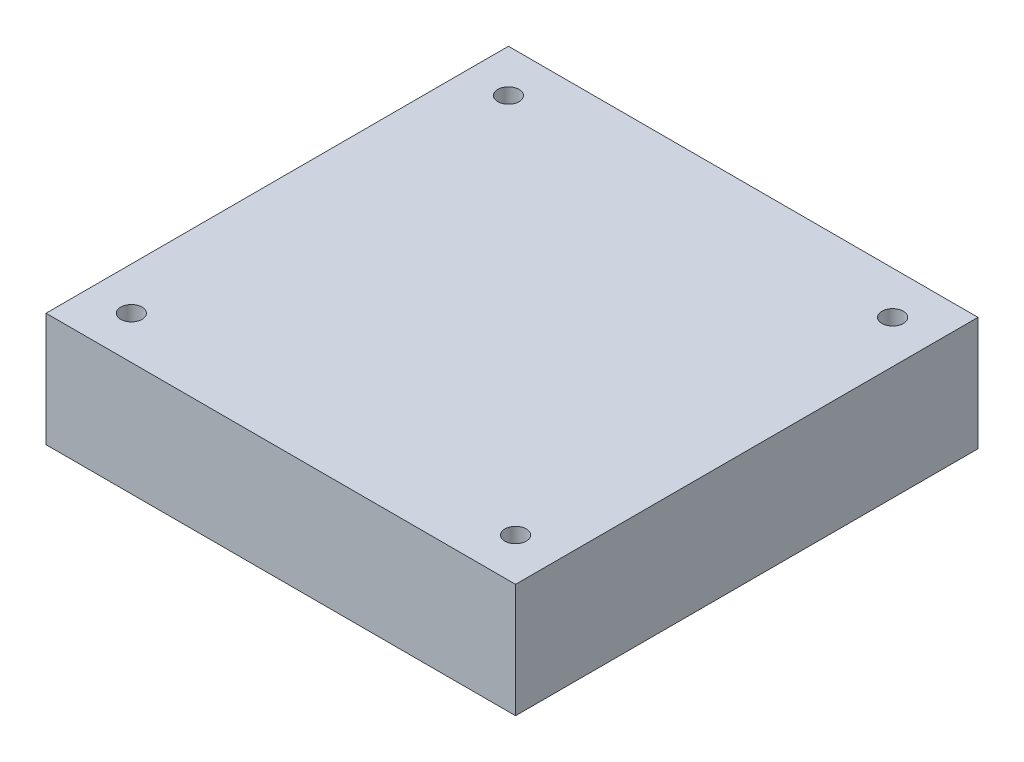
SolidWorks part; units mm, degrees
ref_plane "Front Plane" through (0, 0, 0) normal (0, 0, 1) x (1, 0, 0)
ref_plane "Top Plane" through (0, 0, 0) normal (0, 1, 0) x (1, 0, 0)
ref_plane "Right Plane" through (0, 0, 0) normal (1, 0, 0) x (0, 0, -1)
sketch "Sketch1" plane through (0, 0, 0) normal (0, 1, 0) x (1, 0, 0)
  line L1 (-33, 32.5) -> (33, 32.5)
  line L2 (-33, 32.5) -> (-33, -32.5)
  line L3 (-33, -32.5) -> (33, -32.5)
  line L4 (33, 32.5) -> (33, -32.5)
  line L5 (-33, 32.5) -> (33, -32.5) construction
  line L6 (-33, -32.5) -> (33, 32.5) construction
  point P0 (0, 0)
  dimension "D1" = 66
  dimension "D2" = 65
extrude "Boss-Extrude1" add sketch "Sketch1" along normal blind 16
sketch "Sketch2" plane through (0, 16, 0) normal (0, 1, 0) x (1, 0, 0)
  line L1 (-27, 26.5) -> (27, 26.5) construction
  line L2 (-27, 26.5) -> (-27, -26.5) construction
  line L3 (-27, -26.5) -> (27, -26.5) construction
  line L4 (27, 26.5) -> (27, -26.5) construction
  line L5 (-27, 26.5) -> (27, -26.5) construction
  line L6 (-27, -26.5) -> (27, 26.5) construction
  circle A0 centre (-27, 26.5) radius 1.5
  circle A1 centre (27, 26.5) radius 1.5
  circle A2 centre (27, -26.5) radius 1.5
  circle A3 centre (-27, -26.5) radius 1.5
  point P0 (0, 0)
  dimension "D1" = 3
  dimension "D2" = 54
  dimension "D3" = 53
extrude "Cut-Extrude1" cut sketch "Sketch2" against normal blind 16
